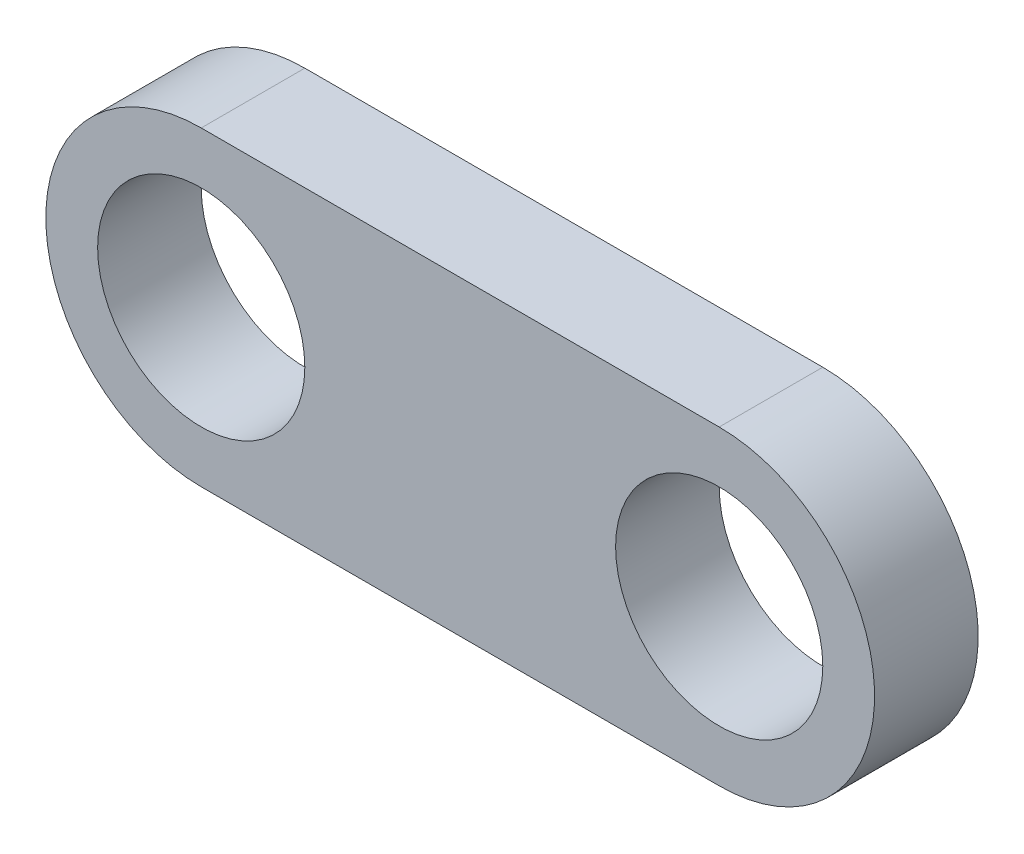
SolidWorks part; units mm, degrees
ref_plane "Front Plane" through (0, 0, 0) normal (0, 0, 1) x (1, 0, 0)
ref_plane "Top Plane" through (0, 0, 0) normal (0, 1, 0) x (1, 0, 0)
ref_plane "Right Plane" through (0, 0, 0) normal (1, 0, 0) x (0, 0, -1)
sketch "Sketch1" plane through (0, 0, 0) normal (0, 0, 1) x (1, 0, 0)
  line L0 (0, 0) -> (50, 0) construction
  line L1 (0, 15) -> (50, 15)
  line L2 (0, -15) -> (50, -15)
  arc A0 (0, 15) -> (0, -15) centre (0, 0) ccw
  arc A1 (50, -15) -> (50, 15) centre (50, 0) ccw
  circle A2 centre (0, 0) radius 10
  circle A3 centre (50, 0) radius 10
  point P3 (25, 0)
  dimension "D1" = 50
  dimension "D2" = 30
extrude "Boss-Extrude1" add sketch "Sketch1" along normal blind 10
